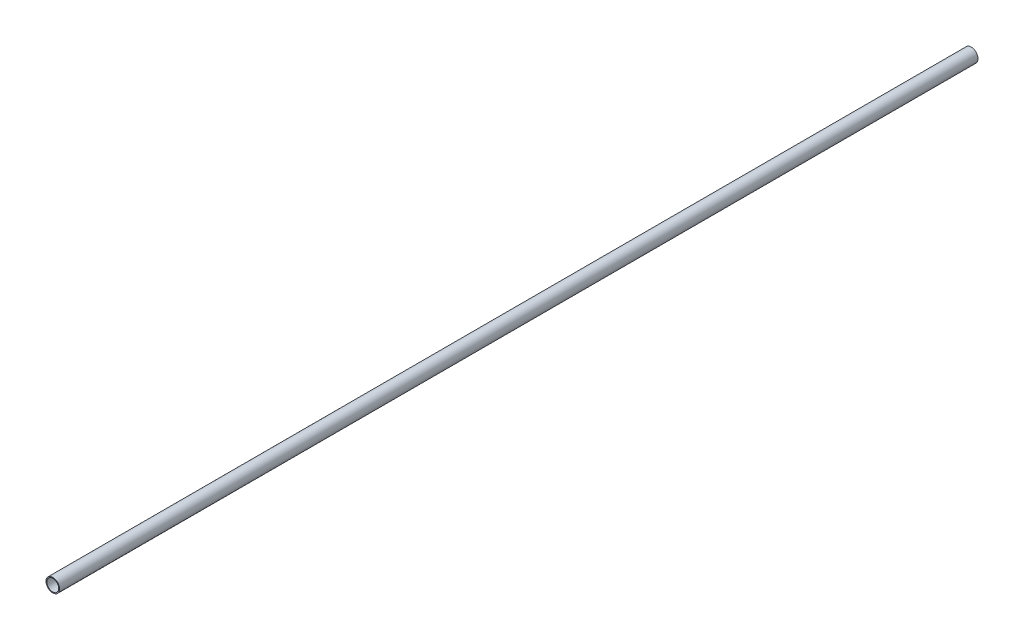
SolidWorks part; units mm, degrees
material "Thornel Mat VMA"
ref_plane "Front" through (0, 0, 0) normal (0, 0, 1) x (1, 0, 0)
ref_plane "Top" through (0, 0, 0) normal (0, 1, 0) x (1, 0, 0)
ref_plane "Right" through (0, 0, 0) normal (1, 0, 0) x (0, 0, -1)
sketch "Sketch1" plane through (0, 0, 0) normal (0, 0, 1) x (1, 0, 0)
  circle A0 centre (0, 0) radius 8.0264
  circle A1 centre (0, 0) radius 7.0104
  dimension "D1" = 16.0528
  dimension "D2" = 1.016
extrude "Boss-Extrude1" add sketch "Sketch1" along normal blind 1085.85
sketch "Sketch2" plane through (0, 0, 0) normal (0, 1, 0) x (1, 0, 0)
  line L0 (8.0264, 0) -> (13.8176, -1016) construction
  line L1 (13.8176, -1016) -> (8.0264, -1016) construction
  line L2 (8.0264, -1085.85) -> (8.0264, 0) construction
  line L3 (0, -1085.85) -> (0, 0) construction
  line L4 (8.0264, 0) -> (8.0264, -1016) construction
  dimension "D1" = 1016
  dimension "D2" = 13.8176
  dimension "D3" = 179.673
ref_plane "Plane1" through (0, 0, 1085.85) normal (0, 0, 1) x (1, 0, 0)
